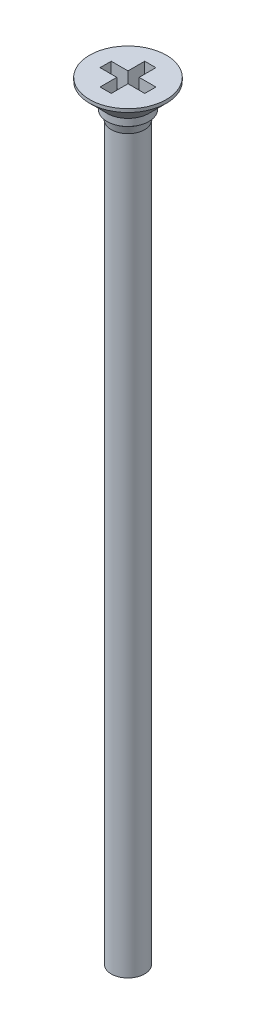
SolidWorks part; units mm, degrees
ref_plane "Vorderseite" through (0, 0, 0) normal (0, 0, 1) x (1, 0, 0)
ref_plane "Oben" through (0, 0, 0) normal (0, 1, 0) x (1, 0, 0)
ref_plane "Rechts" through (0, 0, 0) normal (1, 0, 0) x (0, 0, -1)
sketch "Skizze1" plane through (0, 0, 0) normal (0, 0, 1) x (1, 0, 0)
  line L0 (0, 0) -> (2.75, 0)
  line L1 (2.75, 0) -> (2.75, -0.2375)
  line L2 (2.75, -0.2375) -> (1.5, -1.4875)
  line L3 (1.3375, -1.9875) -> (1.3375, -2.1126)
  line L4 (1.3375, -2.1126) -> (1.1935, -2.65)
  line L5 (1.1935, -2.65) -> (1.1935, -8)
  line L6 (1.1935, -8) -> (0, -8)
  line L7 (0, 0) -> (0, -8) construction
  line L8 (0, 0) -> (0, -8)
  line L10 (1.5, -1.4875) -> (1.5, -1.9875)
  line L12 (1.5, -1.9875) -> (1.3375, -1.9875)
  point P3 (1.3375, -1.65)
  dimension "D1" = 45
  dimension "D2" = 15
  dimension "K" = 1.65
  dimension "DA" = 5.5
  dimension "DK" = 2.387
  dimension "L" = 8
  dimension "DG" = 3
  dimension "A" = 1
  dimension "DF" = 2.675
  dimension "P" = 0.5
revolve "Basis-Rotation" add sketch "Skizze1" angle 360 about L7
sketch "Skizze2" plane through (0, 0, 0) normal (0, 0, 1) x (1, 0, 0)
  line L0 (0, -2.1) -> (0, 0) construction
  line L1 (0, 0) -> (0, -8) construction
  line L2 (-0.55, -2.1) -> (0.55, -2.1)
  line L3 (1.6, 0) -> (1.6, -1.05)
  line L4 (1.6, -1.05) -> (0.55, -2.1)
  line L5 (1.6, 0) -> (-1.6, 0)
  line L6 (-1.6, -1.05) -> (-0.55, -2.1)
  line L7 (-1.6, 0) -> (-1.6, -1.05)
  line L8 (0, -1.05) -> (1.6, -1.05) construction
  line L9 (2.75, 0) -> (-2.75, 0) construction
  line L11 (1.5, -1.4875) -> (2.75, -0.2375) construction
  point P11 (0, 0)
  dimension "M" = 3.2
  dimension "T" = 2.1
extrude "Kreuzschlitz1 H" cut sketch "Skizze2" against normal blind 0.4 and the other way blind 0.4
sketch "Skizze3" plane through (0, 0, 0) normal (1, 0, 0) x (0, 0, -1)
  line L0 (0, -2.1) -> (0, 0) construction
  line L2 (-0.55, -2.1) -> (0.55, -2.1)
  line L3 (1.6, 0) -> (1.6, -1.05)
  line L4 (1.6, -1.05) -> (0.55, -2.1)
  line L5 (1.6, 0) -> (-1.6, 0)
  line L6 (-1.6, -1.05) -> (-0.55, -2.1)
  line L7 (-1.6, 0) -> (-1.6, -1.05)
  line L8 (0, -1.05) -> (1.6, -1.05) construction
  point P11 (0, 0)
extrude "Kreuzschlitz2 H" cut sketch "Skizze3" against normal blind 0.4 and the other way blind 0.4
sketch "Skizze4" plane through (2.4522, 0, -1.8507) normal (0, 1, 0) x (-1, 0, 0)
  line L0 (7.3522, 1.8507) -> (-2.4478, 1.8507) construction
  line L1 (2.4522, -3.0493) -> (2.4522, 6.7507) construction
  line L2 (-2.4478, 1.0342) -> (-2.4478, 2.6672)
  line L3 (-2.4478, 1.0342) -> (0.0059, 1.0342)
  line L4 (0.0059, 1.0342) -> (0.8191, 0.6258)
  line L5 (1.2273, 0.2176) -> (-1.0126, -1.6141)
  line L6 (0.8191, 0.6258) -> (-1.0126, -1.6141)
  line L7 (1.6357, -0.5956) -> (1.2273, 0.2176)
  line L8 (1.6357, -3.0493) -> (1.6357, -0.5956)
  line L9 (1.6357, -3.0493) -> (3.2687, -3.0493)
  line L10 (3.2687, -3.0493) -> (3.2687, -0.5956)
  line L11 (3.2687, -0.5956) -> (3.6772, 0.2176)
  line L12 (2.4522, 1.8507) -> (-1.0126, -1.6141) construction
  line L13 (4.0854, 0.6258) -> (5.917, -1.6141)
  line L14 (3.6772, 0.2176) -> (5.917, -1.6141)
  line L15 (4.8986, 1.0342) -> (4.0854, 0.6258)
  line L16 (7.3522, 1.0342) -> (4.8986, 1.0342)
  line L17 (7.3522, 1.0342) -> (7.3522, 2.6672)
  line L18 (7.3522, 2.6672) -> (4.8986, 2.6672)
  line L19 (4.8986, 2.6672) -> (4.0854, 3.0757)
  line L20 (3.6772, 3.4839) -> (5.917, 5.3156)
  line L21 (4.0854, 3.0757) -> (5.917, 5.3156)
  line L22 (3.2687, 4.2971) -> (3.6772, 3.4839)
  line L23 (3.2687, 6.7507) -> (3.2687, 4.2971)
  line L24 (1.6357, 6.7507) -> (3.2687, 6.7507)
  line L25 (1.6357, 6.7507) -> (1.6357, 4.2971)
  line L26 (1.6357, 4.2971) -> (1.2273, 3.4839)
  line L27 (0.8191, 3.0757) -> (-1.0126, 5.3156)
  line L28 (1.2273, 3.4839) -> (-1.0126, 5.3156)
  line L29 (0.0059, 2.6672) -> (0.8191, 3.0757)
  line L30 (-2.4478, 2.6672) -> (0.0059, 2.6672)
  circle A0 centre (2.4522, 1.8507) radius 4.9 construction
  circle A1 centre (2.4522, 1.8507) radius 2.0415 construction
  circle A2 centre (2.4522, 1.8507) radius 2.579 construction
  dimension "X2" = 4.083
  dimension "X1" = 5.158
  dimension "M" = 9.8
  dimension "D3" = 5.725
  dimension "X3" = 1.633
sketch "Sketch1" plane through (0, -8, 0) normal (0, -1, 0) x (1, 0, 0)
  circle A0 centre (0, 0) radius 1.1935
extrude "Boss-Extrude1" add sketch "Sketch1" along normal blind 47
